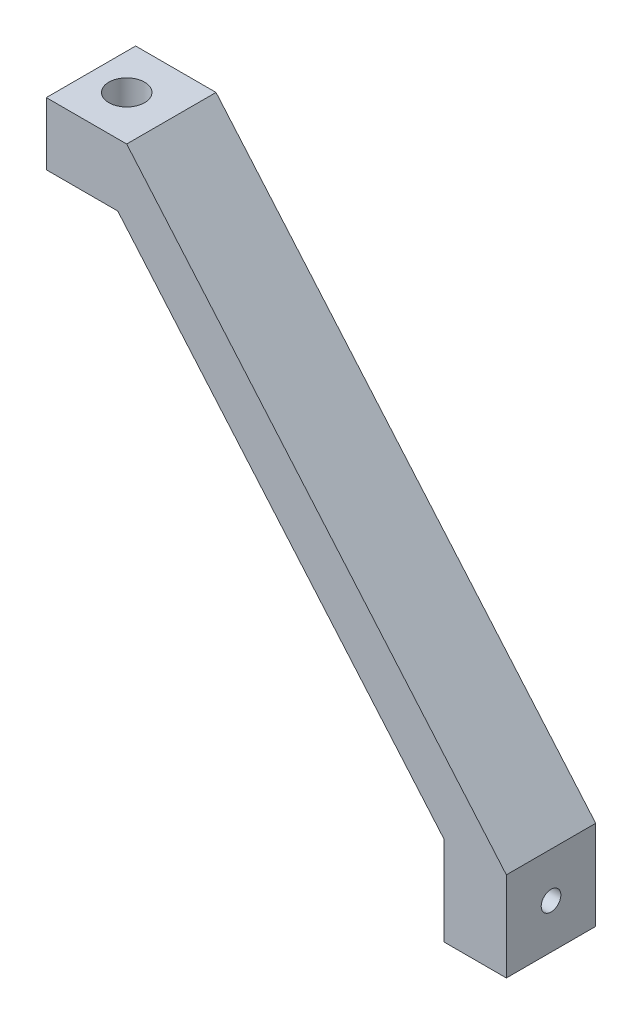
SolidWorks part; units mm, degrees
ref_plane "Alzado" through (0, 0, 0) normal (0, 0, 1) x (1, 0, 0)
ref_plane "Planta" through (0, 0, 0) normal (0, 1, 0) x (1, 0, 0)
ref_plane "Vista lateral" through (0, 0, 0) normal (1, 0, 0) x (0, 0, -1)
sketch "Croquis1" plane through (0, 0, 0) normal (0, 0, 1) x (1, 0, 0)
  line L0 (7, 0) -> (-35.5, 49.6)
  line L1 (0, 0) -> (7, 0)
  line L2 (0, 0) -> (0, -10)
  line L3 (0, -10) -> (7, -10)
  line L4 (7, 0) -> (7, -10)
  line L9 (0, 0) -> (-30, 0) construction
  line L22 (-35.5, 49.6) -> (-44.5, 49.6)
  line L23 (-35.5, 49.6) -> (-35.5, 42.6)
  line L24 (-35.5, 42.6) -> (-44.5, 42.6)
  line L25 (-44.5, 49.6) -> (-44.5, 42.6)
  line L26 (0, 0) -> (-36.4997, 42.6)
  dimension "D1" = 10
  dimension "D2" = 7
  dimension "D3" = 49.408
  dimension "D4" = 49.41
extrude "Saliente-Extruir1" add sketch "Croquis1" along normal blind 10
sketch "Croquis3" plane through (0, 49.6, 0) normal (0, 1, 0) x (1, 0, 0)
  line L0 (-44.5, -5) -> (-40.5, -5) construction
  line L1 (-44.5, -10) -> (-44.5, 0) construction
  circle A0 centre (-40.5, -5) radius 2
extrude "Cortar-Extruir2" cut sketch "Croquis3" against normal blind 10
sketch "Croquis4" plane through (7, 0, 0) normal (1, 0, 0) x (0, 0, -1)
  line L0 (-10, 0) -> (0, -10) construction
  circle A0 centre (-5, -5) radius 1.1
  dimension "D1" = 2.2
extrude "Cortar-Extruir3" cut sketch "Croquis4" against normal blind 10
